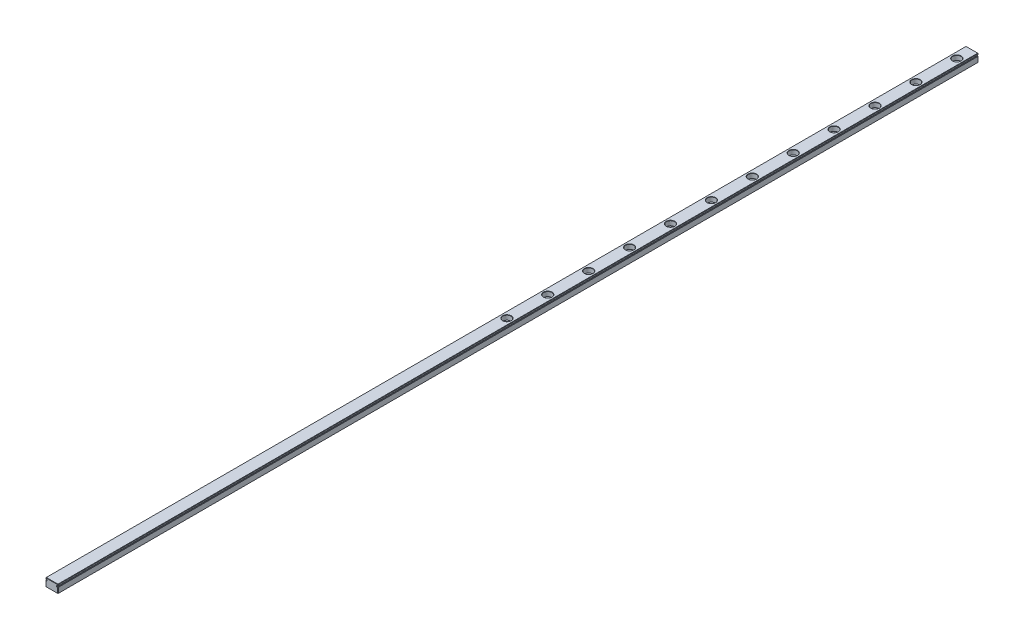
SolidWorks part; units mm, degrees
material "AISI 304"
ref_plane "Front Plane" through (0, 0, 0) normal (0, 0, 1) x (1, 0, 0)
ref_plane "Top Plane" through (0, 0, 0) normal (0, 1, 0) x (1, 0, 0)
ref_plane "Right Plane" through (0, 0, 0) normal (1, 0, 0) x (0, 0, -1)
sketch "Sketch1" plane through (0, 0, 0) normal (0, 0, 1) x (1, 0, 0)
  line L0 (0, 0) -> (0, 8) construction
  line L1 (0, 8) -> (12, 8)
  line L2 (0, 0) -> (12, 0)
  line L3 (0, 8) -> (0, 6.75)
  line L4 (0, 6.75) -> (0.5, 6.25) construction
  line L5 (0.5, 6.25) -> (1, 6.25)
  line L6 (0.5, 5.75) -> (0, 5.25) construction
  line L7 (0, 5.25) -> (0, 0)
  line L8 (1, 6.25) -> (1, 5.75)
  line L9 (1, 5.75) -> (0.5, 5.75)
  line L10 (0.5, 5.75) -> (0.75, 6) construction
  line L11 (0.75, 6) -> (0.5, 6.25) construction
  line L12 (0, 6.75) -> (0, 6.559)
  line L13 (0, 5.25) -> (0, 5.441)
  line L14 (6, 8) -> (6, 0) construction
  line L15 (11.25, 6) -> (11.5, 6.25) construction
  line L16 (11.5, 5.75) -> (11.25, 6) construction
  line L17 (11.5, 5.75) -> (12, 5.25) construction
  line L18 (12, 6.75) -> (11.5, 6.25) construction
  line L19 (12, 0) -> (12, 8) construction
  line L20 (12, 5.25) -> (12, 5.441)
  line L21 (12, 6.75) -> (12, 6.559)
  line L22 (11, 5.75) -> (11.5, 5.75)
  line L23 (11, 6.25) -> (11, 5.75)
  line L24 (12, 5.25) -> (12, 0)
  line L25 (11.5, 6.25) -> (11, 6.25)
  line L26 (12, 8) -> (12, 6.75)
  arc A0 (0, 5.441) -> (0.5, 5.75) centre (0, 6) ccw
  arc A1 (0.5, 6.25) -> (0, 6.559) centre (0, 6) ccw
  arc A2 (11.5, 6.25) -> (12, 6.559) centre (12, 6) cw
  arc A3 (12, 5.441) -> (11.5, 5.75) centre (12, 6) cw
  point P4 (1, 6)
  point P28 (11, 6)
  dimension "D1" = 8
  dimension "D2" = 6
  dimension "D3" = 0.5
  dimension "D4" = 45
  dimension "D5" = 2
  dimension "D6" = 1
extrude "Boss-Extrude1" add sketch "Sketch1" along normal blind 900
chamfer "Chamfer1" distance 0.3 angle 45 36 edges at (0, 0, 450) (12, 0, 450) (0, 8, 450) (12, 8, 450) (0.2939, 5.5245, 900) (0.75, 5.75, 900) (1, 6, 900) (0.75, 6.25, 900) (0.2939, 6.4755, 900) (0, 7.2795, 900) (6, 8, 900) (12, 7.2795, 900) (11.7061, 6.4755, 900) (11.25, 6.25, 900) (11, 6, 900) (11.25, 5.75, 900) (11.7061, 5.5245, 900) (12, 2.7205, 900) (6, 0, 900) (0, 2.7205, 900) (12, 2.7205, 0) (11.7061, 5.5245, 0) (11.25, 5.75, 0) (11, 6, 0) (11.25, 6.25, 0) (11.7061, 6.4755, 0) (12, 7.2795, 0) (6, 0, 0) (0, 2.7205, 0) (0.2939, 5.5245, 0) (0.75, 5.75, 0) (1, 6, 0) (0.75, 6.25, 0) (0.2939, 6.4755, 0) (0, 7.2795, 0) (6, 8, 0)
hole_wizard "CBORE for M5 Hex Head Bolt1" positions "3DSketch1" profile "Sketch3" counterbore size "M5" standard "ANSI Metric" end condition through all
sketch3d "3DSketch1"
  line L0 (6, 8, 0) -> (6, 8, 15) construction
  line L1 (11.7, 8, 0) -> (0.3, 8, 0) construction
  point P0 (6, 8, 15)
  dimension "D1" = 15
sketch "Sketch3" plane through (6, 8, 15) normal (1, 0, 0) x (0, 0, 1)
  line L0 (0, 0) -> (0, 8)
  line L1 (2.25, 7.75) -> (2.5, 8)
  line L2 (4, 4.5) -> (2.25, 4.5)
  line L3 (2.25, 4.5) -> (2.25, 7.75)
  line L5 (4, 4.5) -> (4, 0.25)
  line L6 (4, 0.25) -> (4.25, 0)
  line L7 (4.25, 0) -> (0, 0)
  line L8 (-4, 0.25) -> (-4.25, 0) construction
  line L11 (0, -6.35) -> (0, 107.95) construction
  line L12 (2.5, 8) -> (0, 8)
  line L13 (-2.25, 7.75) -> (-2.5, 8) construction
  dimension "Thru Hole Dia." = 4.5
  dimension "Thru Hole Depth" = 8
  dimension "C'Bore Dia." = 8
  dimension "C'Bore Depth" = 4.5
  dimension "Near C'Sink Dia." = 8.5
  dimension "Near C'Sink Angle" = 90
  dimension "Far C'Sink Dia." = 5
  dimension "Far C'Sink Angle" = 90
pattern_linear "LPattern1" count 12 spacing 40 along (0, 0, 1) of "CBORE for M5 Hex Head Bolt1"
sketch "Sketch4" plane through (0, 0, 900) normal (0, 0, 1) x (1, 0, 0)
  line L0 (6, 0.3) -> (6, 10.6503) construction
  line L1 (0.3, 0.3) -> (11.7, 0.3) construction
sketch "Sketch6" plane through (0, 0, 0) normal (0, 0, -1) x (-1, 0, 0)
  line L0 (-6, 0.3) -> (-6, 11.2574) construction
  line L1 (-11.7, 0.3) -> (-0.3, 0.3) construction
